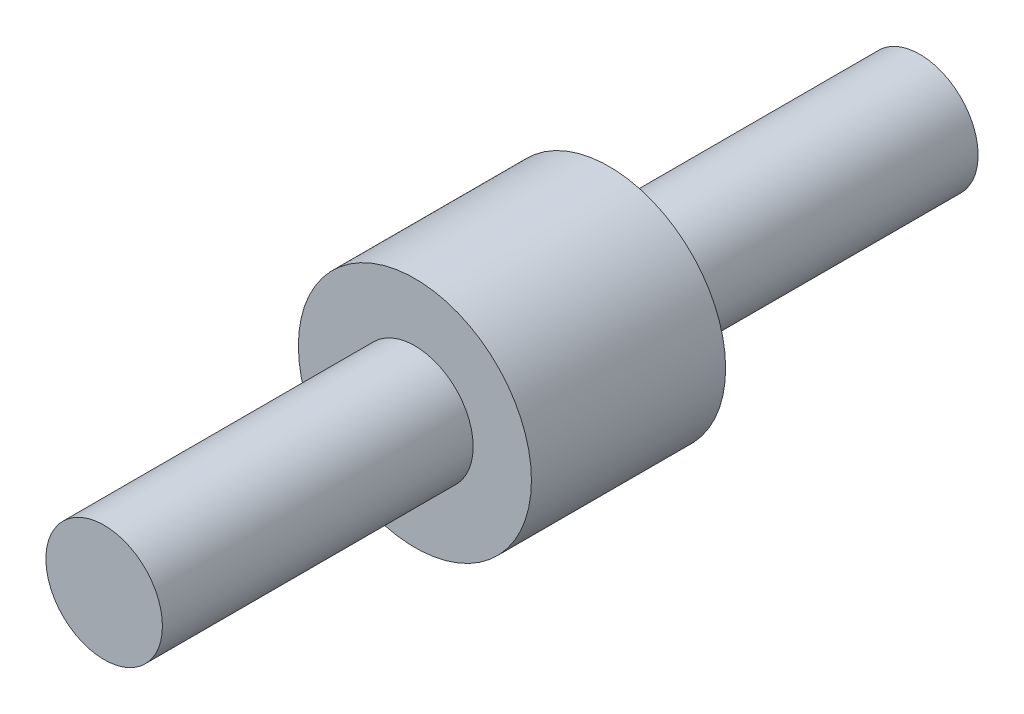
SolidWorks part; units mm, degrees
ref_plane "Płaszczyzna przednia" through (0, 0, 0) normal (0, 0, 1) x (1, 0, 0)
ref_plane "Płaszczyzna górna" through (0, 0, 0) normal (0, 1, 0) x (1, 0, 0)
ref_plane "Płaszczyzna prawa" through (0, 0, 0) normal (1, 0, 0) x (0, 0, -1)
sketch "Sketch1" plane through (0, 0, 0) normal (0, 0, 1) x (1, 0, 0)
  line L0 (-5, 0) -> (0, 0) construction
  line L1 (0, 0) -> (0, -5) construction
  circle A2 centre (0, 0) radius 3
  dimension "D1" = 6
extrude "Boss-Extrude1 dlugosc calkowita S4" add sketch "Sketch1" along normal blind 5
sketch "Sketch2" plane through (0, 0, 0) normal (0, 0, -1) x (-1, 0, 0)
  circle A1 centre (0, 0) radius 1.5
  circle A3 centre (0, 0) radius 3 construction
  dimension "D1" = 3
extrude "Boss-Extrude2 przedluzenie do montazu" add sketch "Sketch2" along normal blind 8 and the other way offset from surface (13 mm away) 8 other way up to face at (3, 0, 5)
sketch "koniec1" plane through (0, 0, 0) normal (0, 0, -1) x (-1, 0, 0)
  line L0 (-3, 0) -> (0, 0) construction
  line L2 (0, 0) -> (0, 3) construction
  circle A3 centre (0, 0) radius 3 construction
sketch "koniec2" plane through (0, 0, 5) normal (0, 0, 1) x (1, 0, 0)
  line L0 (0, 3) -> (0, 0) construction
  line L1 (0, 0) -> (3, 0) construction
  circle A0 centre (0, 0) radius 3 construction
equation "\"D1@Boss-Extrude1 dlugosc calkowita S4\" = \"dlugosc S3\""
equation "\"dlugosc S3\"=5"
equation "\"dlugosc S4\"= 150"
equation "\"dlugosc S1\"= 1"
equation "\"dlugosc S2\"= 50"
